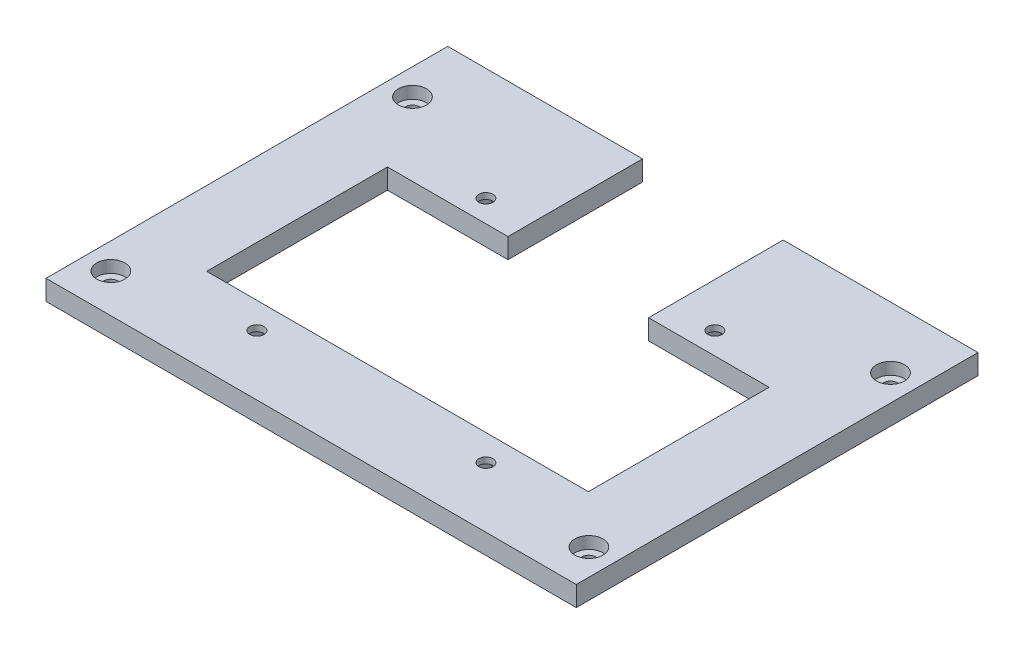
SolidWorks part; units mm, degrees
ref_plane "Front Plane" through (0, 0, 0) normal (0, 0, 1) x (1, 0, 0)
ref_plane "Top Plane" through (0, 0, 0) normal (0, 1, 0) x (1, 0, 0)
ref_plane "Right Plane" through (0, 0, 0) normal (1, 0, 0) x (0, 0, -1)
sketch "Sketch1" plane through (0, 0, 0) normal (0, 1, 0) x (1, 0, 0)
  line L1 (-66, 50) -> (66, 50)
  line L2 (-66, 50) -> (-66, -50)
  line L3 (-66, -50) -> (66, -50)
  line L4 (66, 50) -> (66, -50)
  line L5 (0, -50) -> (0, 50) construction
  line L6 (-66, 0) -> (66, 0) construction
  point P4 (0, 0)
  point P160 (0, 0)
  dimension "D1" = 132
  dimension "D2" = 100
extrude "Boss-Extrude1" add sketch "Sketch1" along normal blind 5
sketch "Sketch2" plane through (0, 5, 0) normal (0, 1, 0) x (1, 0, 0)
  line L0 (-59.5, 34.72) -> (59.5, 34.72) construction
  line L1 (59.5, 34.72) -> (59.5, -40.36) construction
  line L2 (59.5, -40.36) -> (-59.5, -40.36) construction
  line L3 (-59.5, -40.36) -> (-59.5, 34.72) construction
  line L4 (-66, 50) -> (-66, -50) construction
  line L5 (66, 50) -> (-66, 50) construction
  circle A0 centre (-59.5, 34.72) radius 1.75
  circle A1 centre (-59.5, -40.36) radius 1.75
  circle A2 centre (59.5, -40.36) radius 1.75
  circle A3 centre (59.5, 34.72) radius 1.75
  dimension "D1" = 3.5
  dimension "D2" = 3.5
  dimension "D3" = 3.5
  dimension "D4" = 3.5
  dimension "D8" = 15.28
  dimension "D5" = 75.08
  dimension "D6" = 119
  dimension "D7" = 6.5
extrude "Cut-Extrude1" cut sketch "Sketch2" against normal blind 56
sketch "Sketch3" plane through (0, 5, 0) normal (0, 1, 0) x (1, 0, 0)
  line L0 (66, 50) -> (-66, 50) construction
  line L1 (-17.5, 50) -> (17.5, 50)
  line L2 (-17.5, 50) -> (-17.5, 16.5)
  line L4 (17.5, 50) -> (17.5, 16.5)
  line L7 (17.5, 16.5) -> (47.5, 16.5)
  line L8 (-47.5, 16.5) -> (-17.5, 16.5)
  line L9 (-47.5, 16.5) -> (-47.5, -28.5)
  line L10 (-47.5, -28.5) -> (47.5, -28.5)
  line L11 (47.5, 16.5) -> (47.5, -28.5)
  point P7 (0, 50)
  point P180 (0, 16.5)
  point P252 (0, -6)
  dimension "D1" = 35
  dimension "D3" = 30
  dimension "D4" = 30
  dimension "D5" = 95
  dimension "D6" = 45
sketch "Sketch4" plane through (0, 5, 0) normal (0, 1, 0) x (1, 0, 0)
  line L0 (-28.5, 22) -> (28.5, 22) construction
  line L1 (28.5, 22) -> (28.5, -35) construction
  line L2 (28.5, -35) -> (-28.5, -35) construction
  line L3 (-28.5, -35) -> (-28.5, 22) construction
  line L4 (66, 50) -> (-66, 50) construction
  line L5 (0, 22) -> (0, 50) construction
  circle A0 centre (-28.5, 22) radius 1.75
  circle A1 centre (-28.5, -35) radius 1.75
  circle A2 centre (28.5, -35) radius 1.75
  circle A3 centre (28.5, 22) radius 1.75
  dimension "D1" = 57
  dimension "D2" = 57
  dimension "D3" = 28
  dimension "D5" = 3.5
  dimension "D6" = 3.5
  dimension "D7" = 3.5
  dimension "D8" = 3.5
extrude "Cut-Extrude4" cut sketch "Sketch3" against normal blind 103
extrude "Cut-Extrude5" cut sketch "Sketch4" against normal blind 103
sketch "Sketch6" plane through (0, 5, 0) normal (0, 1, 0) x (1, 0, 0)
  circle A0 centre (-59.5, 34.72) radius 3.5
  circle A1 centre (-59.5, -40.36) radius 3.5
  circle A2 centre (59.5, -40.36) radius 3.5
  circle A3 centre (59.5, 34.72) radius 3.5
  dimension "D1" = 7
  dimension "D2" = 7
  dimension "D3" = 7
  dimension "D4" = 7
extrude "Cut-Extrude6" cut sketch "Sketch6" against normal blind 3
sketch "Sketch7" plane through (0, 0, 0) normal (0, -1, 0) x (1, 0, 0)
  line L1 (26.4793, -25.5) -> (30.5207, -25.5)
  line L2 (30.5207, -25.5) -> (32.5415, -22)
  line L3 (32.5415, -22) -> (30.5207, -18.5)
  line L4 (30.5207, -18.5) -> (26.4793, -18.5)
  line L5 (26.4793, -18.5) -> (24.4585, -22)
  line L6 (24.4585, -22) -> (26.4793, -25.5)
  line L7 (24.4585, 35) -> (26.4793, 31.5)
  line L8 (26.4793, 31.5) -> (30.5207, 31.5)
  line L9 (30.5207, 31.5) -> (32.5415, 35)
  line L10 (32.5415, 35) -> (30.5207, 38.5)
  line L11 (30.5207, 38.5) -> (26.4793, 38.5)
  line L12 (26.4793, 38.5) -> (24.4585, 35)
  line L13 (-30.5207, 38.5) -> (-32.5415, 35)
  line L14 (-32.5415, 35) -> (-30.5207, 31.5)
  line L15 (-30.5207, 31.5) -> (-26.4793, 31.5)
  line L16 (-26.4793, 31.5) -> (-24.4585, 35)
  line L17 (-24.4585, 35) -> (-26.4793, 38.5)
  line L18 (-26.4793, 38.5) -> (-30.5207, 38.5)
  line L19 (-32.5415, -22) -> (-30.5207, -25.5)
  line L20 (-30.5207, -25.5) -> (-26.4793, -25.5)
  line L21 (-26.4793, -25.5) -> (-24.4585, -22)
  line L22 (-24.4585, -22) -> (-26.4793, -18.5)
  line L23 (-26.4793, -18.5) -> (-30.5207, -18.5)
  line L24 (-30.5207, -18.5) -> (-32.5415, -22)
  circle A0 centre (28.5, -22) radius 3.5 construction
  circle A1 centre (28.5, 35) radius 3.5 construction
  circle A2 centre (-28.5, 35) radius 3.5 construction
  circle A3 centre (-28.5, -22) radius 3.5 construction
  point P28 (-25.4689, 33.25)
  dimension "D1" = 7
  dimension "D2" = 7
  dimension "D3" = 7
  dimension "D4" = 7
extrude "Cut-Extrude7" cut sketch "Sketch7" against normal blind 3.5
